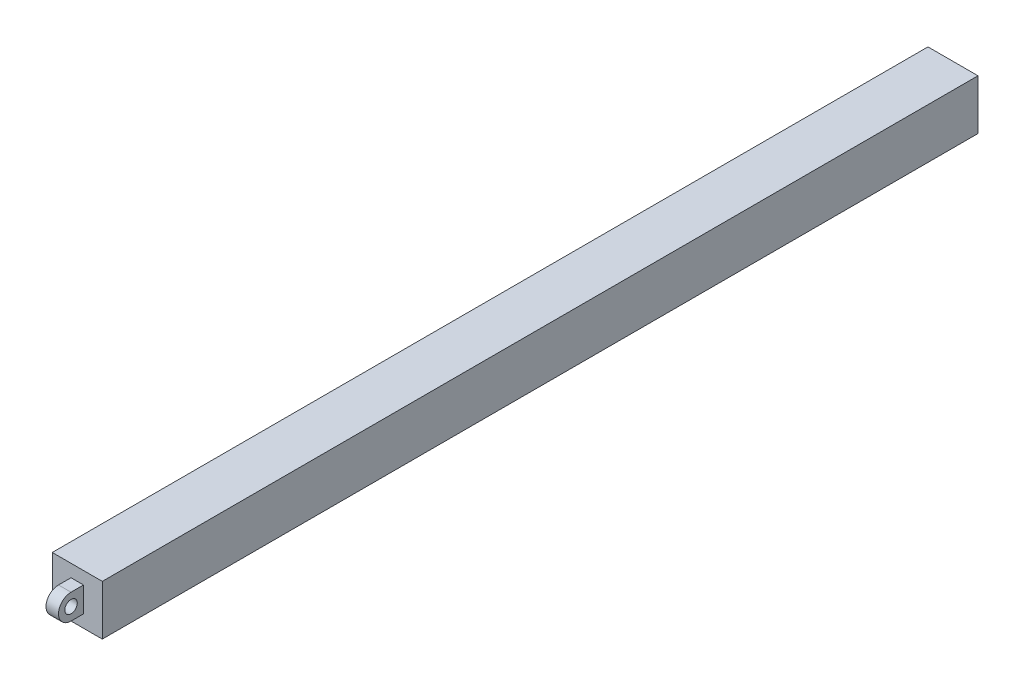
SolidWorks part; units mm, degrees
ref_plane "정면" through (0, 0, 0) normal (0, 0, 1) x (1, 0, 0)
ref_plane "윗면" through (0, 0, 0) normal (0, 1, 0) x (1, 0, 0)
ref_plane "우측면" through (0, 0, 0) normal (1, 0, 0) x (0, 0, -1)
sketch "스케치2" plane through (0, 0, 0) normal (1, 0, 0) x (0, 0, -1)
  line L0 (0, 5) -> (0, -5) construction
  line L1 (-87.5, 5) -> (87.5, 5)
  line L2 (-87.5, 5) -> (-87.5, -5)
  line L3 (-87.5, -5) -> (87.5, -5)
  line L4 (87.5, 5) -> (87.5, -5)
  line L5 (-87.5, 0) -> (87.5, 0) construction
  dimension "D1" = 10
  dimension "D2" = 175
extrude "보스-돌출1" add sketch "스케치2" along normal mid plane 10
sketch "스케치3" plane through (0, 0, 0) normal (1, 0, 0) x (0, 0, -1)
  line L0 (-87.5, 5) -> (-87.5, -5) construction
  line L1 (-90, 2.5) -> (-87.5, 2.5)
  line L2 (0, 0) -> (-168.2672, 0) construction
  line L3 (-90, -2.5) -> (-87.5, -2.5)
  line L4 (-87.5, 2.5) -> (-87.5, -2.5)
  arc A0 (-90, 2.5) -> (-90, -2.5) centre (-90, 0) ccw
  circle A1 centre (-90, 0) radius 1.25
  dimension "D3" = 2.5
  dimension "D1" = 5
  dimension "D2" = 2.5
extrude "보스-돌출2" add sketch "스케치3" along normal mid plane 2.5
